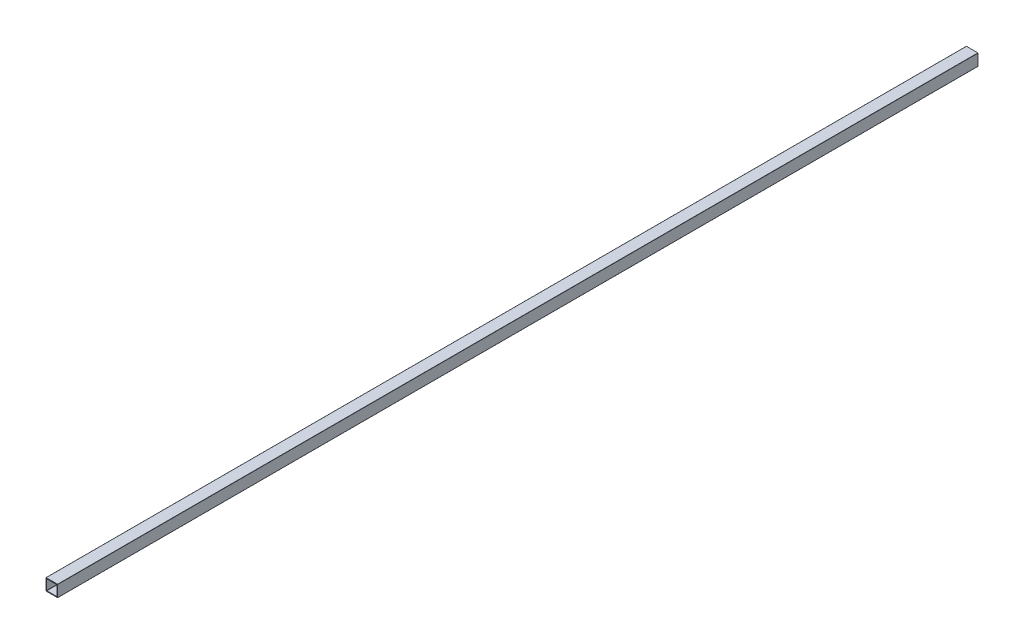
SolidWorks part; units mm, degrees
material "AISI 1035 Acero (SS)"
ref_plane "Alzado" through (0, 0, 0) normal (0, 0, 1) x (1, 0, 0)
ref_plane "Planta" through (0, 0, 0) normal (0, 1, 0) x (1, 0, 0)
ref_plane "Vista lateral" through (0, 0, 0) normal (1, 0, 0) x (0, 0, -1)
sketch "Croquis1" plane through (0, 0, 0) normal (0, 0, 1) x (1, 0, 0)
  line L0 (-33.55, -33.55) -> (-33.55, 33.55)
  line L1 (-38.1, -38.1) -> (38.1, -38.1)
  line L2 (-38.1, -38.1) -> (-38.1, 38.1)
  line L3 (-38.1, 38.1) -> (38.1, 38.1)
  line L4 (38.1, -38.1) -> (38.1, 38.1)
  line L5 (-38.1, -38.1) -> (38.1, 38.1) construction
  line L6 (-38.1, 38.1) -> (38.1, -38.1) construction
  line L7 (-33.55, 33.55) -> (33.55, 33.55)
  line L8 (33.55, -33.55) -> (33.55, 33.55)
  line L9 (-33.55, -33.55) -> (33.55, -33.55)
  point P0 (0, 0)
  dimension "D1" = 76.2
  dimension "D3" = 4.55
extrude "Saliente-Extruir1" add sketch "Croquis1" against normal blind 6000
fillet "Redondeo1" radius 1 8 edges at (-33.55, 33.55, -3000) (33.55, 33.55, -3000) (33.55, -33.55, -3000) (-38.1, -38.1, -3000) (-38.1, 38.1, -3000) (-33.55, -33.55, -3000) (38.1, -38.1, -3000) (38.1, 38.1, -3000)
